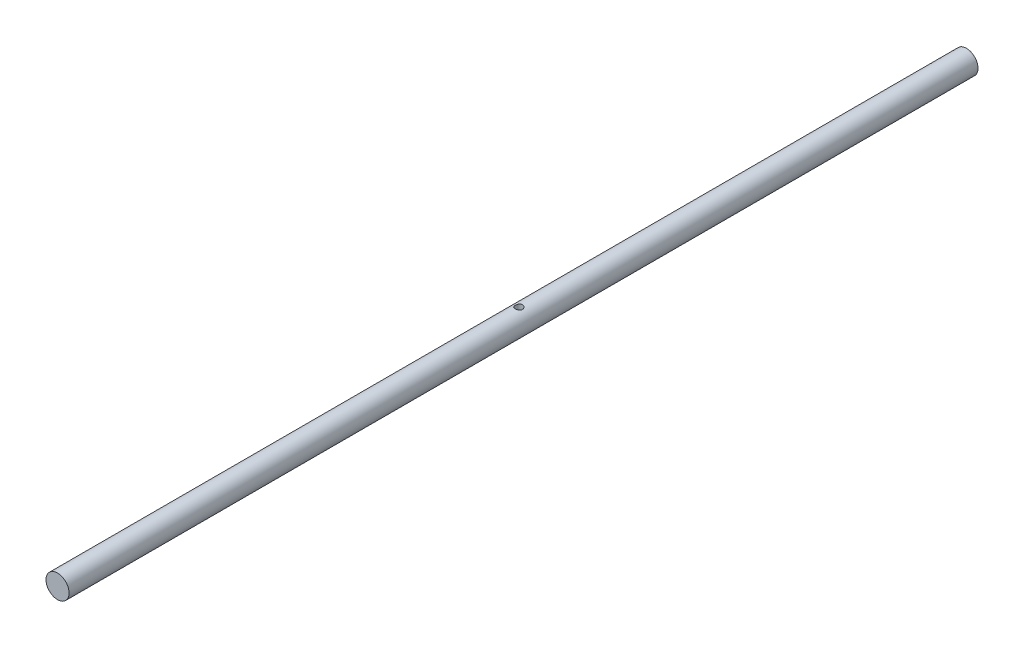
SolidWorks part; units mm, degrees
ref_plane "Front Plane" through (0, 0, 0) normal (0, 0, 1) x (1, 0, 0)
ref_plane "Top Plane" through (0, 0, 0) normal (0, 1, 0) x (1, 0, 0)
ref_plane "Right Plane" through (0, 0, 0) normal (1, 0, 0) x (0, 0, -1)
sketch "Sketch1" plane through (0, 0, 0) normal (0, 0, 1) x (1, 0, 0)
  circle A0 centre (0, 0) radius 12.7
  dimension "D1" = 25.4
extrude "Boss-Extrude1" add sketch "Sketch1" along normal blind 1000
sketch "Sketch2" plane through (0, 0, 0) normal (0, 1, 0) x (1, 0, 0)
  line L0 (0, 0) -> (0, 104.6862) construction
  line L1 (-228.4777, -500) -> (426.8942, -500) construction
  line L2 (12.7, 0) -> (-12.7, 0) construction
  circle A0 centre (0, -492.5) radius 3.9688
  dimension "D3" = 7.9375
  dimension "D1" = 0
  dimension "D2" = 500
  dimension "D4" = 7.5
extrude "Cut-Extrude1" cut sketch "Sketch2" against normal through all both and the other way through all
